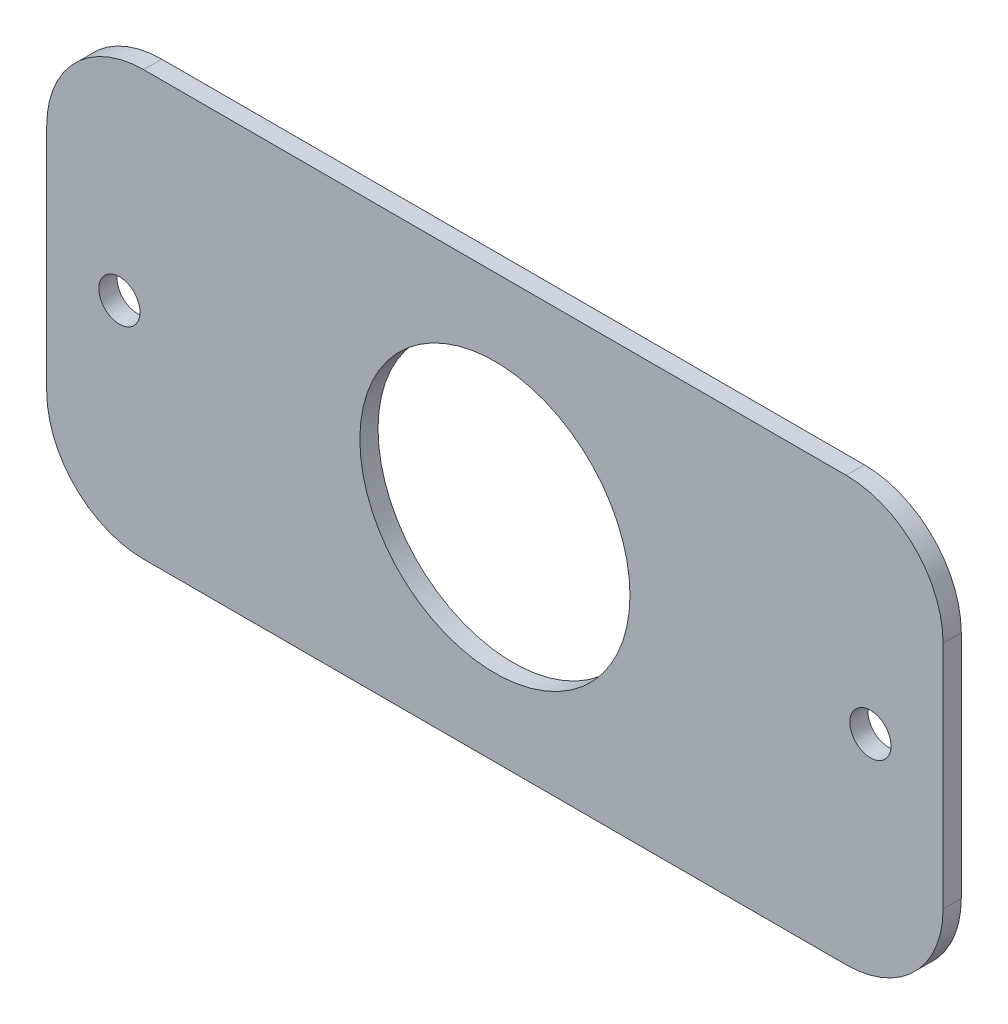
SolidWorks part; units mm, degrees
ref_plane "Plan de face" through (0, 0, 0) normal (0, 0, 1) x (1, 0, 0)
ref_plane "Plan de dessus" through (0, 0, 0) normal (0, 1, 0) x (1, 0, 0)
ref_plane "Plan de droite" through (0, 0, 0) normal (1, 0, 0) x (0, 0, -1)
sketch "Esquisse1" plane through (0, 0, 0) normal (0, 0, 1) x (1, 0, 0)
  line L1 (0, 0) -> (74, 0)
  line L2 (0, 0) -> (0, 35)
  line L3 (0, 35) -> (74, 35)
  line L4 (74, 0) -> (74, 35)
  circle A0 centre (37, 17.5) radius 11.15
  circle A1 centre (6, 17.5) radius 1.5
  circle A2 centre (68, 17.5) radius 1.5
  dimension "D1" = 22.3
  dimension "D8" = 3
  dimension "D11" = 3
  dimension "D2" = 35
  dimension "D3" = 17.5
  dimension "D4" = 74
  dimension "D5" = 37
  dimension "D6" = 17.5
  dimension "D7" = 17.5
  dimension "D9" = 6
  dimension "D10" = 6
extrude "Boss.-Extru.1" add sketch "Esquisse1" along normal blind 1.5
hole_wizard "Dégagement M31" positions "Esquisse4" profile "Esquisse5" hole size "M3" standard "ISO" end condition up to next
sketch "Esquisse4" plane through (0, 0, 1.5) normal (0, 0, 1) x (1, 0, 0)
  point P0 (6, 17.5)
  point P3 (68, 17.5)
sketch "Esquisse5" plane through (6, 17.5, 1.5) normal (1, 0, 0) x (0, -1, 0)
  line L0 (0, 0) -> (0, 1.5)
  line L1 (0, 1.5) -> (1.7, 1.5)
  line L2 (1.7, 1.5) -> (1.7, 0)
  line L5 (1.7, 0) -> (0, 0)
  line L11 (0, -6.35) -> (0, 107.95) construction
  dimension "Diamètre du perçage jusqu'au prochain" = 3.4
  dimension "Profondeur du perçage jusqu'au prochain" = 1.5
fillet "Congé1" radius 8 4 edges at (0, 35, 0.75) (74, 35, 0.75) (74, 0, 0.75) (0, 0, 0.75)
equation "\"D3@Esquisse1\"=\"D2@Esquisse1\"/2"
equation "\"D5@Esquisse1\"=\"D4@Esquisse1\"/2"
equation "\"D6@Esquisse1\"=\"D2@Esquisse1\"/2"
equation "\"D7@Esquisse1\"=\"D2@Esquisse1\"/2"
